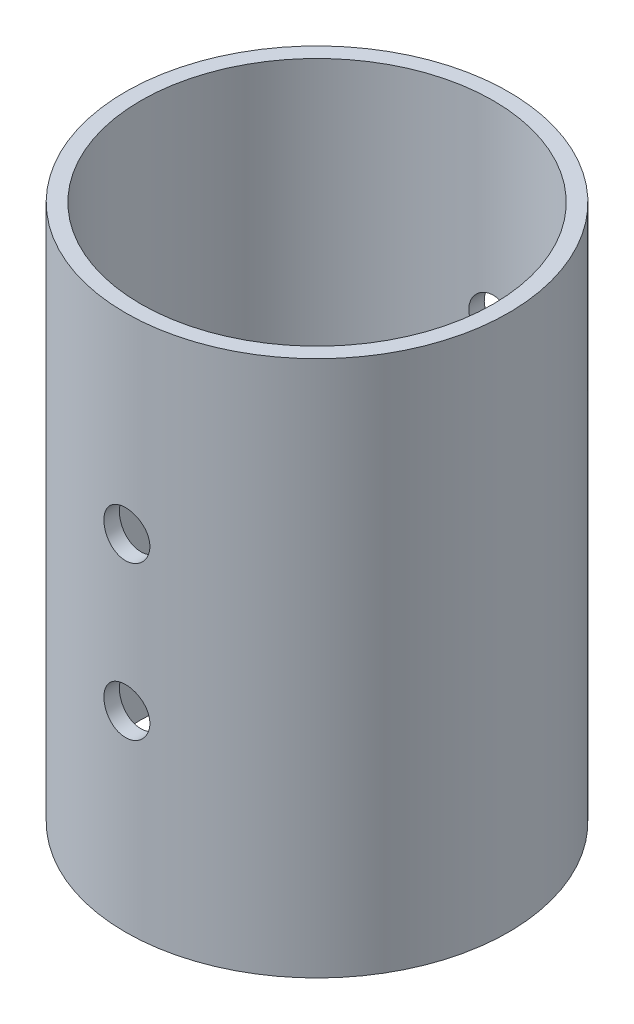
SolidWorks part; units mm, degrees
material "Thornel Mat VMA"
ref_plane "前视基准面" through (0, 0, 0) normal (0, 0, 1) x (1, 0, 0)
ref_plane "上视基准面" through (0, 0, 0) normal (0, 1, 0) x (1, 0, 0)
ref_plane "右视基准面" through (0, 0, 0) normal (1, 0, 0) x (0, 0, -1)
other "Configuration Table"
sketch "草图1" plane through (0, 0, 0) normal (0, 1, 0) x (1, 0, 0)
  circle A0 centre (0, 0) radius 25
  circle A1 centre (0, 0) radius 23
  dimension "D1" = 50
  dimension "D2" = 46
extrude "凸台-拉伸1" add sketch "草图1" along normal blind 70
sketch "草图2" plane through (0, 0, 0) normal (0, 0, 1) x (1, 0, 0)
  line L0 (-25, 70) -> (25, 0) construction
  line L1 (25, 70) -> (-25, 0) construction
  line L2 (0, 25) -> (0, 45) construction
  circle A0 centre (0, 45) radius 3
  circle A1 centre (0, 25) radius 3
  point P12 (0, 35)
  dimension "D2" = 6
  dimension "D3" = 6
  dimension "D1" = 20
extrude "切除-拉伸1" cut sketch "草图2" against normal through all and the other way through all
